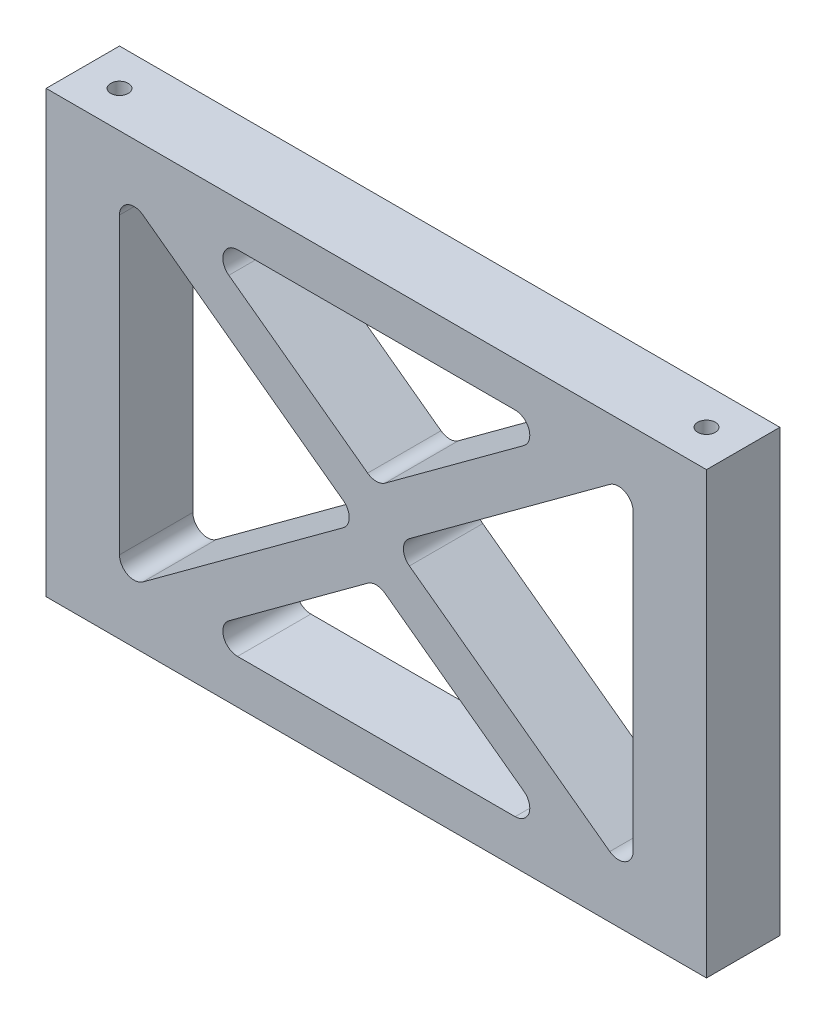
SolidWorks part; units mm, degrees
ref_plane "Ebene vorne" through (0, 0, 0) normal (0, 0, 1) x (1, 0, 0)
ref_plane "Ebene oben" through (0, 0, 0) normal (0, 1, 0) x (1, 0, 0)
ref_plane "Ebene rechts" through (0, 0, 0) normal (1, 0, 0) x (0, 0, -1)
sketch "Skizze1" plane through (0, 0, 0) normal (0, 0, 1) x (1, 0, 0)
  line L1 (0, 0) -> (90, 0)
  line L2 (0, 0) -> (0, 60)
  line L3 (0, 60) -> (90, 60)
  line L4 (90, 0) -> (90, 60)
  dimension "D1" = 90
  dimension "D2" = 60
extrude "Aufsatz-Linear austragen1" add sketch "Skizze1" along normal blind 10
sketch "Skizze2" plane through (0, 0, 10) normal (0, 0, 1) x (1, 0, 0)
  line L0 (10, 50.0503) -> (10, 9.9497)
  line L1 (45, 51.6277) -> (45, -7.4804) construction
  line L2 (13.1837, 51.6625) -> (40.4918, 31.6121)
  line L4 (43.8163, 36.4993) -> (24.9005, 50.3879)
  line L5 (26.0841, 54) -> (63.9159, 54)
  line L6 (90, 60) -> (0, 60) construction
  line L8 (0, 60) -> (0, 0) construction
  line L9 (-2.0593, 30) -> (95.2495, 30) construction
  line L10 (26.0841, 6) -> (63.9159, 6)
  line L11 (43.8163, 23.5007) -> (24.9005, 9.6121)
  line L12 (13.1837, 8.3375) -> (40.4918, 28.3879)
  line L13 (46.1837, 36.4993) -> (65.0995, 50.3879)
  line L14 (46.1837, 23.5007) -> (65.0995, 9.6121)
  line L15 (80, 50.0503) -> (80, 9.9497)
  line L16 (76.8163, 8.3375) -> (49.5082, 28.3879)
  line L17 (76.8163, 51.6625) -> (49.5082, 31.6121)
  line L18 (90, 0) -> (90, 60) construction
  arc A0 (80, 9.9497) -> (76.8163, 8.3375) centre (78, 9.9497) cw
  arc A1 (80, 50.0503) -> (76.8163, 51.6625) centre (78, 50.0503) ccw
  arc A2 (49.5082, 28.3879) -> (49.5082, 31.6121) centre (50.6919, 30) cw
  arc A3 (65.0995, 9.6121) -> (63.9159, 6) centre (63.9159, 8) cw
  arc A4 (26.0841, 6) -> (24.9005, 9.6121) centre (26.0841, 8) cw
  arc A5 (43.8163, 23.5007) -> (46.1837, 23.5007) centre (45, 21.8885) cw
  arc A6 (65.0995, 50.3879) -> (63.9159, 54) centre (63.9159, 52) ccw
  arc A7 (43.8163, 36.4993) -> (46.1837, 36.4993) centre (45, 38.1115) ccw
  arc A8 (24.9005, 50.3879) -> (26.0841, 54) centre (26.0841, 52) cw
  arc A9 (40.4918, 31.6121) -> (40.4918, 28.3879) centre (39.3081, 30) cw
  arc A10 (13.1837, 8.3375) -> (10, 9.9497) centre (12, 9.9497) cw
  arc A11 (10, 50.0503) -> (13.1837, 51.6625) centre (12, 50.0503) cw
  point P1 (0, 0)
  point P19 (10, 30)
  point P20 (45, 54)
  point P21 (45, 6)
  point P30 (80, 6)
  point P33 (80, 54)
  point P36 (47.3126, 30)
  point P39 (70.0192, 6)
  point P42 (19.9808, 6)
  point P45 (45, 24.3697)
  point P48 (70.0192, 54)
  point P51 (45, 35.6303)
  point P54 (19.9808, 54)
  point P57 (42.6874, 30)
  point P60 (10, 6)
  point P63 (10, 54)
  dimension "D5" = 2
  dimension "D1" = 6
  dimension "D2" = 6
  dimension "D3" = 10
  dimension "D4" = 10
extrude "Schnitt-Linear austragen1" cut sketch "Skizze2" against normal blind 10
sketch "Skizze3" plane through (0, 60, 0) normal (0, 1, 0) x (1, 0, 0)
  line L0 (90, -10) -> (90, 0) construction
  line L1 (0, -10) -> (0, 0) construction
  line L2 (90, -10) -> (0, -10) construction
  circle A0 centre (5, -5) radius 1.2
  circle A1 centre (85, -5) radius 1.2
  dimension "D1" = 2.4
  dimension "D2" = 2.4
  dimension "D3" = 5
  dimension "D4" = 5
  dimension "D5" = 5
  dimension "D6" = 5
extrude "Schnitt-Linear austragen2" cut sketch "Skizze3" against normal blind 84
